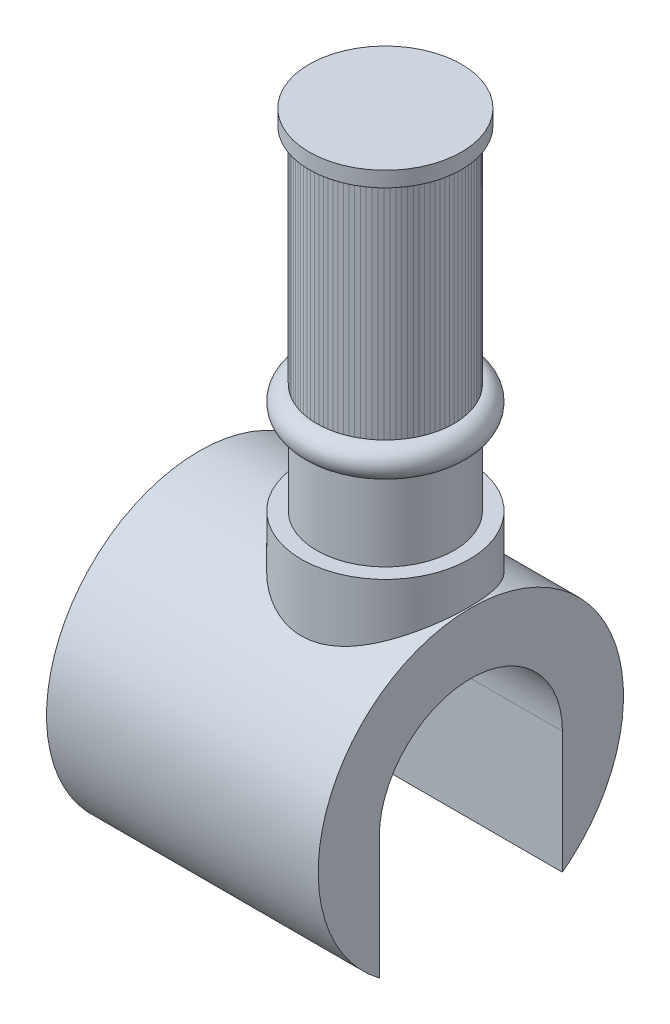
SolidWorks part; units mm, degrees
ref_plane "Front Plane" through (0, 0, 0) normal (0, 0, 1) x (1, 0, 0)
ref_plane "Top Plane" through (0, 0, 0) normal (0, 1, 0) x (1, 0, 0)
ref_plane "Right Plane" through (0, 0, 0) normal (1, 0, 0) x (0, 0, -1)
sketch "Sketch4" plane through (0, 0, 0) normal (0, 0, 1) x (1, 0, 0)
  line L0 (0, 4.0609) -> (0, -2.7127) construction
  line L1 (0, 3.7873) -> (1.125, 3.7873)
  line L2 (1.125, 3.7873) -> (1.125, 0.1873)
  line L3 (1.125, -0.3127) -> (1.125, -1.6127)
  line L4 (1.125, -1.6127) -> (1.375, -1.6127)
  line L5 (1.375, -1.6127) -> (1.375, -2.7127)
  line L6 (1.375, -2.7127) -> (0, -2.7127)
  line L7 (0, 3.7873) -> (0, -2.7127)
  arc A0 (1.125, 0.1873) -> (1.125, -0.3127) centre (1.125, -0.0627) cw
  dimension "D3" = 0.25
  dimension "D1" = 1.125
  dimension "D2" = 3.6
  dimension "D4" = 1.3
  dimension "D5" = 0.25
  dimension "D6" = 1.1
revolve "Revolve1" add sketch "Sketch4" angle 360 about L0
sketch "Sketch6" plane through (0, 0, 0) normal (1, 0, 0) x (0, 0, -1)
  line L0 (0, 0) -> (0, -5.3664) construction
  line L1 (0, -5.3664) -> (-2.5, -4.7892) construction
  circle A0 centre (0, -4.7892) radius 2.5
  dimension "D1" = 5
  dimension "D2" = 77
extrude "Boss-Extrude3" add sketch "Sketch6" along normal blind 1.4 and the other way blind 3.05
sketch "Sketch7" plane through (-3.05, 0, 0) normal (-1, 0, 0) x (0, 0, 1)
  line L0 (-1.5, -4.7892) -> (-1.5, -7.5708)
  line L1 (-1.5, -7.5708) -> (1.5, -7.5708)
  line L2 (1.5, -4.7892) -> (1.5, -7.5708)
  arc A0 (1.5, -4.7892) -> (-1.5, -4.7892) centre (0, -4.7892) ccw
  dimension "D1" = 3
  dimension "D2" = 3
extrude "Cut-Extrude1" cut sketch "Sketch7" against normal blind 4.45
sketch "Sketch2" plane through (0, 0, 0) normal (0, 1, 0) x (1, 0, 0)
  circle A0 centre (0, 0) radius 1.125
  dimension "D1" = 2.25
extrude "Boss-Extrude1" add sketch "Sketch2" along normal blind 3.85
sketch "Sketch3" plane through (0, 3.85, 0) normal (0, 1, 0) x (1, 0, 0)
  circle A0 centre (0, 0) radius 1.2468
  dimension "D1" = 2.4937
extrude "Boss-Extrude2" add sketch "Sketch3" along normal blind 0.25
